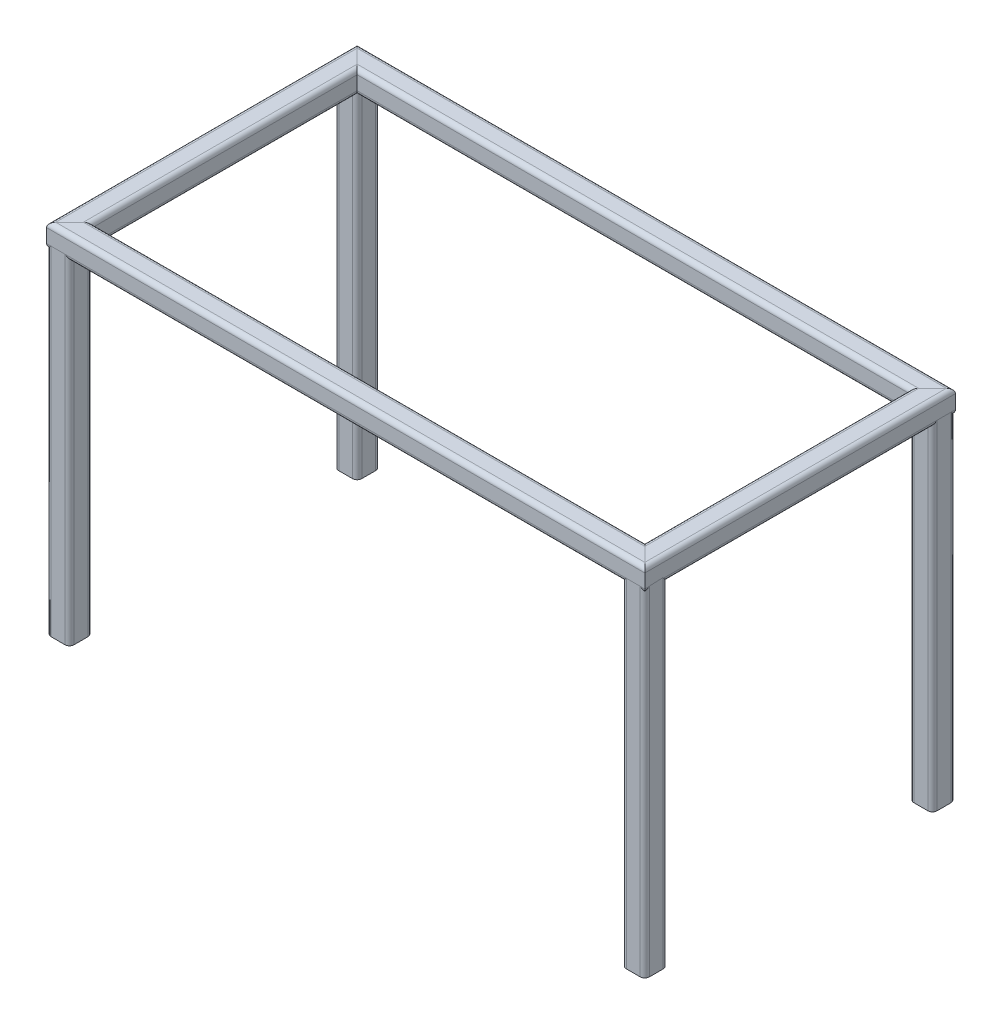
SolidWorks part; units mm, degrees
other "DetailItem2"
other "Weld Folder"
other "Weld Bead2"
ref_plane "Front Plane" through (0, 0, 0) normal (0, 0, 1) x (1, 0, 0)
ref_plane "Top Plane" through (0, 0, 0) normal (0, 1, 0) x (1, 0, 0)
ref_plane "Right Plane" through (0, 0, 0) normal (1, 0, 0) x (0, 0, -1)
sketch3d "3DSketch2"
  line L1 (0, 0, 0) -> (0, 0, 500)
  line L2 (0, 0, 0) -> (1000, 0, 0)
  line L3 (1000, 0, 0) -> (1000, 0, 500)
  line L4 (0, 0, 500) -> (1000, 0, 500)
  dimension "D1" = 1000
  dimension "D2" = 500
sketch3d "3DSketch5"
  line L0 (0, 0, 500) -> (0, -600, 500)
  line L1 (1000, 0, 500) -> (1000, -600, 500)
  line L2 (1000, 0, 0) -> (1000, -600, 0)
  line L3 (0, 0, 0) -> (0, -600, 0)
  dimension "D1" = 600
other "Square tube 40 X 40 X 4(1)"
ref_plane "Plane1" through (0, 0, 0) normal (0, 0, 1) x (1, 0, 0)
sketch "Sketch1" plane through (0, 0, 0) normal (0, 0, 1) x (1, 0, 0)
  line L0 (-12, -16) -> (12, -16)
  line L1 (-16, -12) -> (-16, 12)
  line L2 (12, 16) -> (-12, 16)
  line L3 (16, 12) -> (16, -12)
  line L4 (-12, -20) -> (12, -20)
  line L5 (-20, -12) -> (-20, 12)
  line L6 (12, 20) -> (-12, 20)
  line L7 (20, 12) -> (20, -12)
  arc A0 (20, 12) -> (12, 20) centre (12, 12) ccw
  arc A1 (12, -20) -> (20, -12) centre (12, -12) ccw
  arc A2 (-20, -12) -> (-12, -20) centre (-12, -12) ccw
  arc A3 (-12, 20) -> (-20, 12) centre (-12, 12) ccw
  arc A4 (-12, 16) -> (-16, 12) centre (-12, 12) ccw
  arc A5 (16, 12) -> (12, 16) centre (12, 12) ccw
  arc A6 (12, -16) -> (16, -12) centre (12, -12) ccw
  arc A7 (-16, -12) -> (-12, -16) centre (-12, -12) ccw
  point P0 (-20, 0)
  point P1 (20, 0)
  point P2 (0, 20)
  point P3 (0, -20)
  point P4 (0, 0)
  point P5 (-20, -20)
  point P6 (20, -20)
  point P7 (20, 20)
  point P8 (-20, 20)
  point P33 (0, 0)
  dimension "D1" = 8
  dimension "Thickness" = 4
  dimension "V_leg" = 40
other "Square tube 40 X 40 X 4(2)"
ref_plane "Plane2" through (0, 0, 500) normal (0, -1, 0) x (1, 0, 0)
sketch "Sketch11" plane through (0, 0, 500) normal (0, -1, 0) x (1, 0, 0)
  line L0 (-12, -16) -> (12, -16)
  line L1 (-16, -12) -> (-16, 12)
  line L2 (12, 16) -> (-12, 16)
  line L3 (16, 12) -> (16, -12)
  line L4 (-12, -20) -> (12, -20)
  line L5 (-20, -12) -> (-20, 12)
  line L6 (12, 20) -> (-12, 20)
  line L7 (20, 12) -> (20, -12)
  arc A0 (20, 12) -> (12, 20) centre (12, 12) ccw
  arc A1 (12, -20) -> (20, -12) centre (12, -12) ccw
  arc A2 (-20, -12) -> (-12, -20) centre (-12, -12) ccw
  arc A3 (-12, 20) -> (-20, 12) centre (-12, 12) ccw
  arc A4 (-12, 16) -> (-16, 12) centre (-12, 12) ccw
  arc A5 (16, 12) -> (12, 16) centre (12, 12) ccw
  arc A6 (12, -16) -> (16, -12) centre (12, -12) ccw
  arc A7 (-16, -12) -> (-12, -16) centre (-12, -12) ccw
  point P0 (-20, 0)
  point P1 (20, 0)
  point P2 (0, 20)
  point P3 (0, -20)
  point P4 (0, 0)
  point P5 (-20, -20)
  point P6 (20, -20)
  point P7 (20, 20)
  point P8 (-20, 20)
  point P33 (0, 0)
  dimension "D1" = 8
  dimension "Thickness" = 4
  dimension "V_leg" = 40
